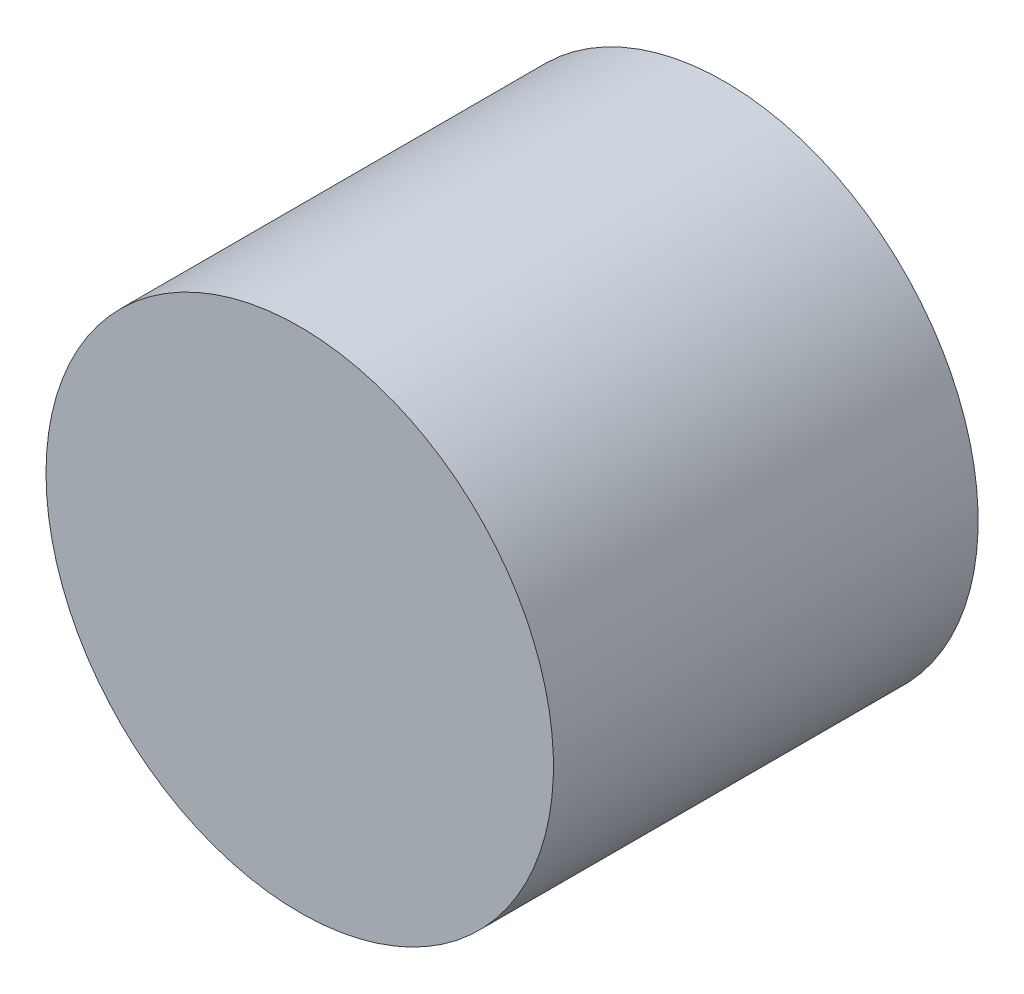
SolidWorks part; units mm, degrees
ref_plane "Plane1" through (0, 0, 0) normal (0, 0, 1) x (1, 0, 0)
ref_plane "Plane2" through (0, 0, 0) normal (0, 1, 0) x (1, 0, 0)
ref_plane "Plane3" through (0, 0, 0) normal (1, 0, 0) x (0, 0, -1)
other "Configuration Table"
sketch "Sketch1" plane through (0, 0, 0) normal (0, 0, 1) x (1, 0, 0)
  circle A0 centre (-0.7394, 0.6843) radius 4.6 construction
  circle A2 centre (-0.7394, 0.6843) radius 4.6
extrude "rubber feet" add sketch "Sketch1" along normal blind 7.7
